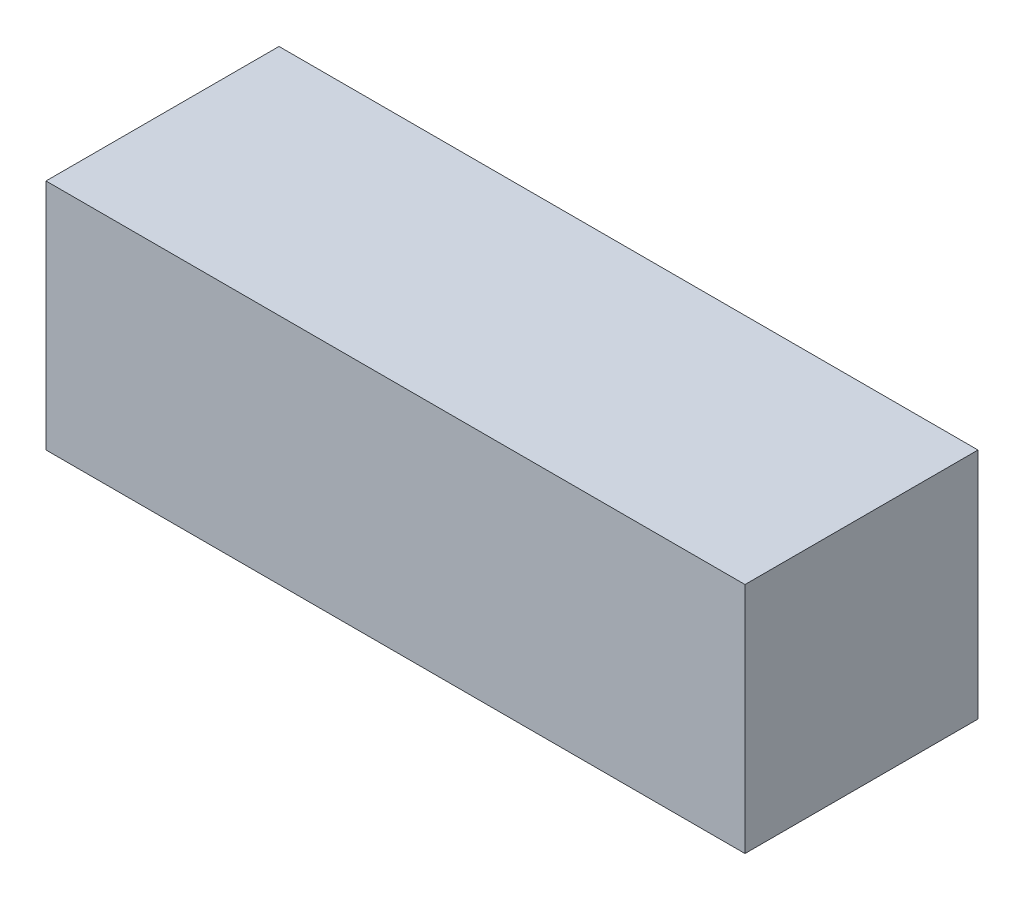
SolidWorks part; units mm, degrees
ref_plane "Front Plane" through (0, 0, 0) normal (0, 0, 1) x (1, 0, 0)
ref_plane "Top Plane" through (0, 0, 0) normal (0, 1, 0) x (1, 0, 0)
ref_plane "Right Plane" through (0, 0, 0) normal (1, 0, 0) x (0, 0, -1)
other "Center of Mass"
sketch "Sketch1" plane through (0, 0, 0) normal (0, 1, 0) x (1, 0, 0)
  line L1 (0, 0) -> (152.4, 0)
  line L2 (0, 0) -> (0, 50.8)
  line L3 (0, 50.8) -> (152.4, 50.8)
  line L4 (152.4, 0) -> (152.4, 50.8)
  dimension "D1" = 152.4
  dimension "D2" = 50.8
extrude "Boss-Extrude1" add sketch "Sketch1" along normal blind 50.8 contours L2 L3 L4 L1
equation "\"Batt_Length\"=6"
equation "\"D1@Sketch1\"=\"Batt_Length\""
equation "\"Batt_Height\"=2"
equation "\"D2@Sketch1\"=\"Batt_Height\""
equation "\"Batt_Depth\"=2"
equation "\"D1@Boss-Extrude1\"=\"Batt_Depth\""
